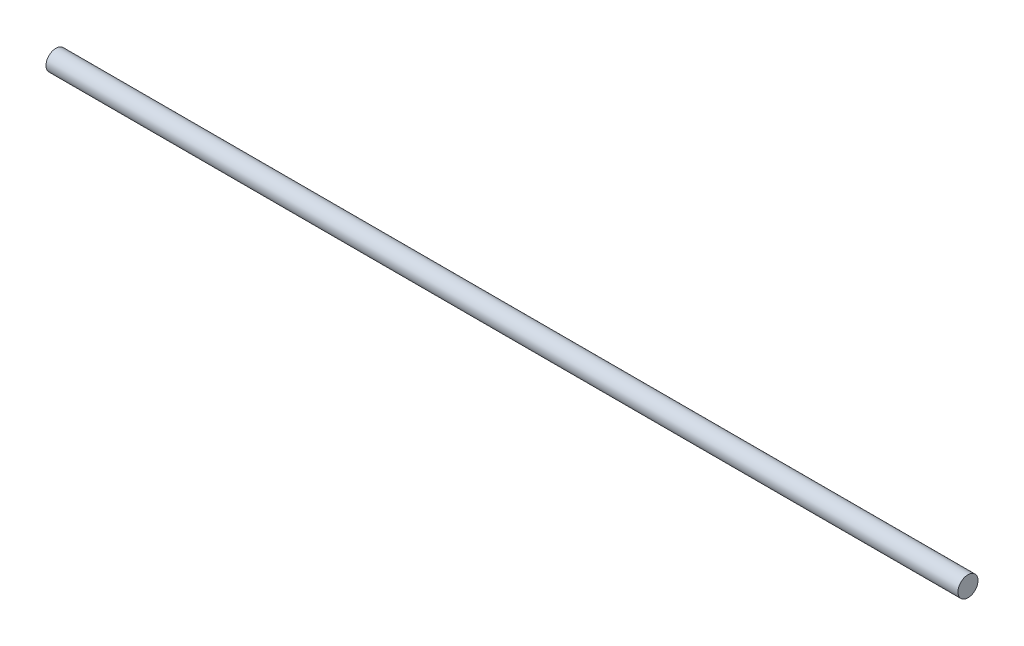
SolidWorks part; units mm, degrees
ref_plane "Front Plane" through (0, 0, 0) normal (0, 0, 1) x (1, 0, 0)
ref_plane "Top Plane" through (0, 0, 0) normal (0, 1, 0) x (1, 0, 0)
ref_plane "Right Plane" through (0, 0, 0) normal (1, 0, 0) x (0, 0, -1)
sketch "Sketch2" plane through (0, 0, 0) normal (1, 0, 0) x (0, 0, -1)
  circle A0 centre (0, 0) radius 3.175
  dimension "D1" = 6.35
extrude "Boss-Extrude1" add sketch "Sketch2" along normal blind 288.925
